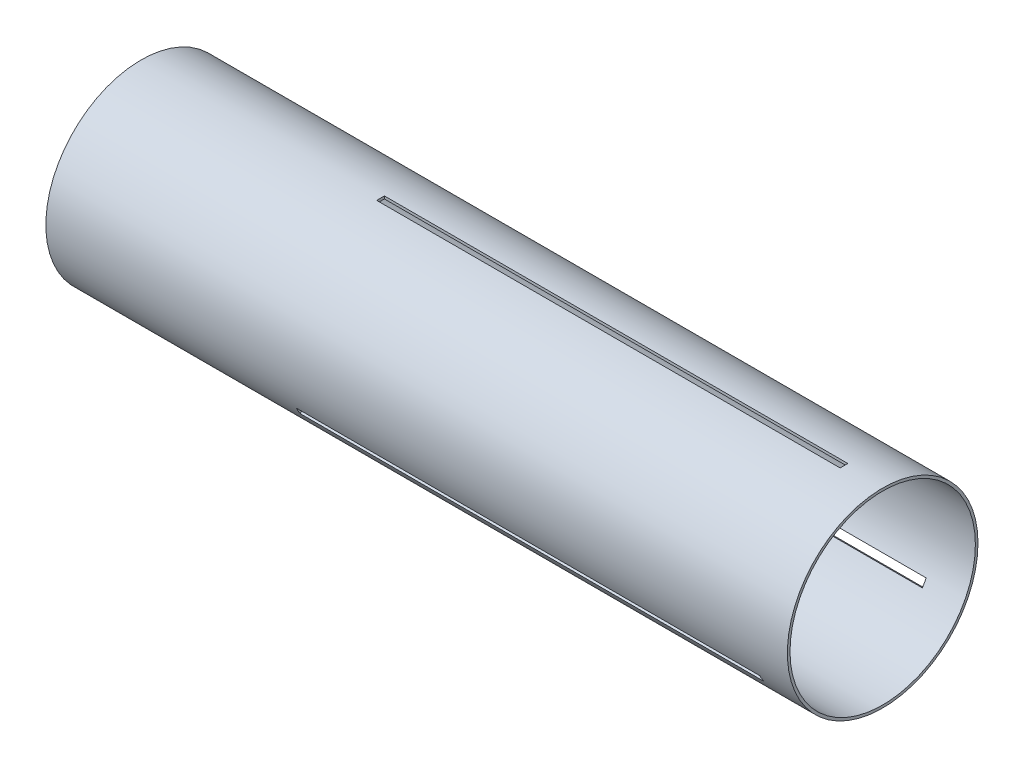
SolidWorks part; units mm, degrees
material "E-Glass Fiber"
ref_plane "Front Plane" through (0, 0, 0) normal (0, 0, 1) x (1, 0, 0)
ref_plane "Top Plane" through (0, 0, 0) normal (0, 1, 0) x (1, 0, 0)
ref_plane "Right Plane" through (0, 0, 0) normal (1, 0, 0) x (0, 0, -1)
sketch "Sketch1" plane through (0, 0, 0) normal (1, 0, 0) x (0, 0, -1)
  circle A0 centre (0, 0) radius 76.2
  circle A1 centre (0, 0) radius 78.359
  dimension "D1" = 156.718
  dimension "D2" = 152.4
extrude "Boss-Extrude1" add sketch "Sketch1" along normal blind 609.6
ref_plane "Plane1" through (577.85, 0, 0) normal (1, 0, 0) x (0, 0, -1)
sketch "Sketch3" plane through (577.85, 0, 0) normal (1, 0, 0) x (0, 0, -1)
  line L0 (-3.175, 78.2947) -> (-3.175, 76.1338)
  line L1 (3.175, 78.2947) -> (3.175, 76.1338)
  circle A0 centre (0, 0) radius 78.359 construction
  circle A1 centre (0, 0) radius 76.2 construction
  arc A2 (3.175, 76.1338) -> (-3.175, 76.1338) centre (0, 0) ccw
  arc A3 (3.175, 78.2947) -> (-3.175, 78.2947) centre (0, 0) ccw
  dimension "D1" = 6.35
extrude "Cut-Extrude1" cut sketch "Sketch3" against normal blind 381
pattern_circular "CirPattern1" count 3 over 360 about axis through (0, 0, 0) along (1, 0, 0) of "Cut-Extrude1"
